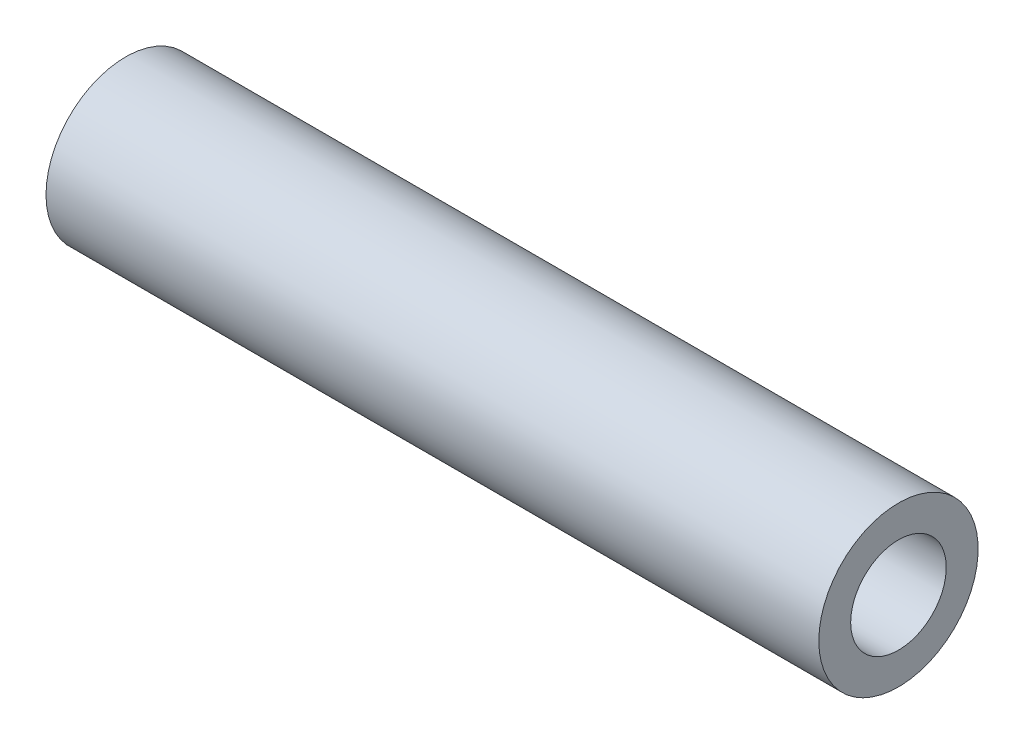
SolidWorks part; units mm, degrees
ref_plane "Front Plane" through (0, 0, 0) normal (0, 0, 1) x (1, 0, 0)
ref_plane "Top Plane" through (0, 0, 0) normal (0, 1, 0) x (1, 0, 0)
ref_plane "Right Plane" through (0, 0, 0) normal (1, 0, 0) x (0, 0, -1)
sketch "Sketch2" plane through (8.6, 0, 0) normal (-1, 0, 0) x (0, 0, 1)
  circle A0 centre (15.5819, 50.7926) radius 2.5
  circle A1 centre (15.5819, 50.7926) radius 1.5
  circle A2 centre (15.5819, 50.7926) radius 1.5 construction
  dimension "D1" = 5
extrude "Boss-Extrude1" add sketch "Sketch2" along normal up to surface (24.25 mm away)
